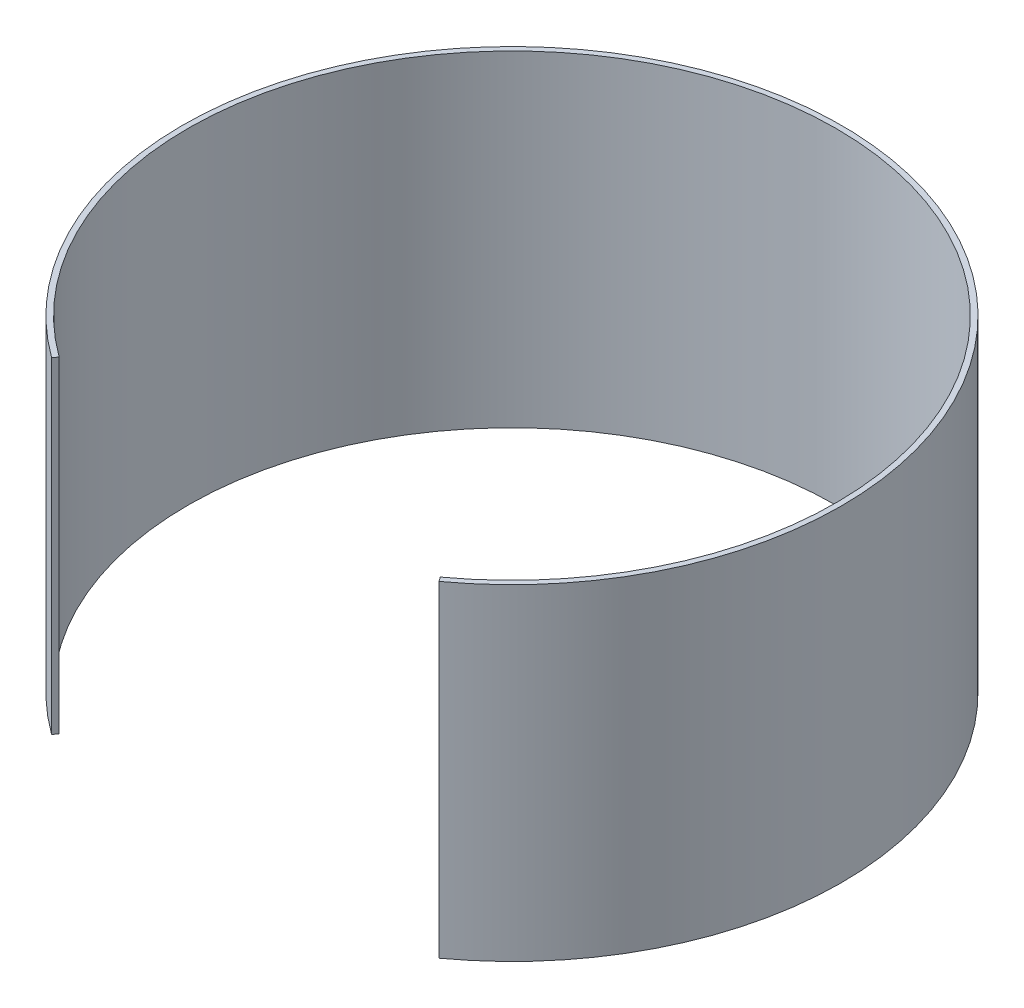
SolidWorks part; units mm, degrees
ref_plane "Front Plane" through (0, 0, 0) normal (0, 0, 1) x (1, 0, 0)
ref_plane "Top Plane" through (0, 0, 0) normal (0, 1, 0) x (1, 0, 0)
ref_plane "Right Plane" through (0, 0, 0) normal (1, 0, 0) x (0, 0, -1)
sketch "Sketch1" plane through (0, 0, 0) normal (0, 1, 0) x (1, 0, 0)
  line L2 (176.3356, -242.7051) -> (179.2745, -246.7502)
  line L3 (-176.3356, -242.7051) -> (-179.2745, -246.7502)
  arc A0 (179.2745, -246.7502) -> (-179.2745, -246.7502) centre (0, 0) ccw
  arc A1 (176.3356, -242.7051) -> (-176.3356, -242.7051) centre (0, 0) ccw
  point P4 (-175.8502, -242.037)
  point P6 (175.8502, -242.037)
  dimension "D1" = 600
  dimension "D2" = 610
extrude "Boss-Extrude2" add sketch "Sketch1" along normal blind 302
